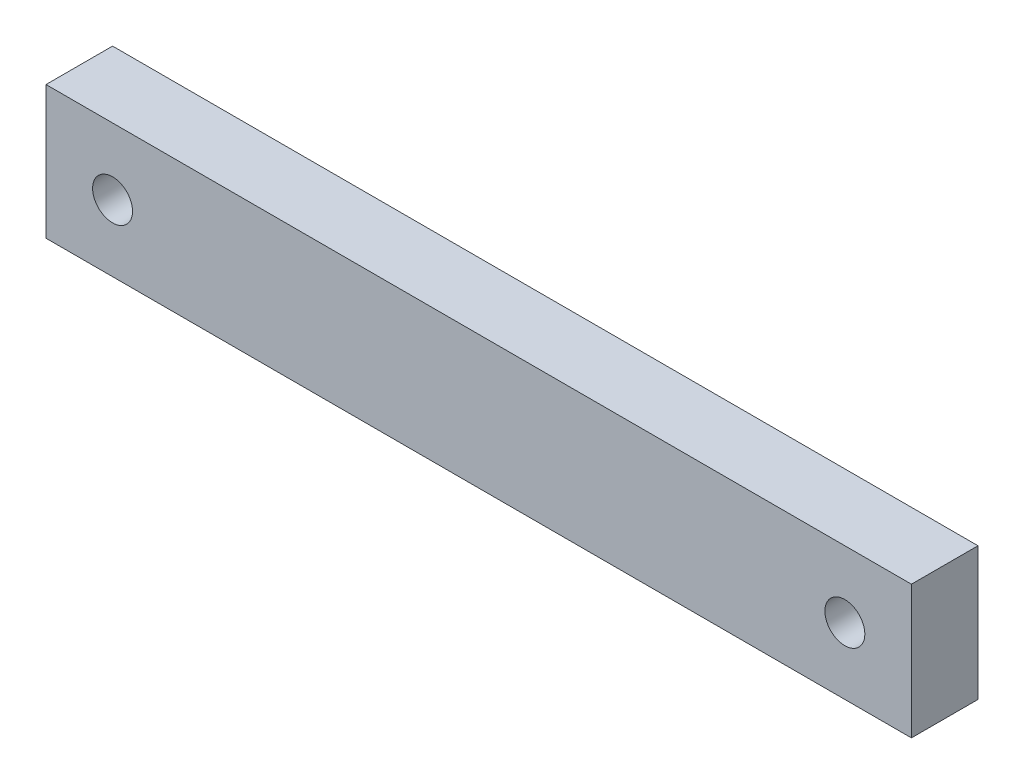
SolidWorks part; units mm, degrees
ref_plane "Front Plane" through (0, 0, 0) normal (0, 0, 1) x (1, 0, 0)
ref_plane "Top Plane" through (0, 0, 0) normal (0, 1, 0) x (1, 0, 0)
ref_plane "Right Plane" through (0, 0, 0) normal (1, 0, 0) x (0, 0, -1)
sketch "Sketch1" plane through (0, 0, 0) normal (0, 0, 1) x (1, 0, 0)
  line L0 (0, 0) -> (27.5, 0)
  line L1 (-32.5, 5) -> (32.5, 5)
  line L2 (-32.5, 5) -> (-32.5, -5)
  line L3 (-32.5, -5) -> (32.5, -5)
  line L4 (32.5, 5) -> (32.5, -5)
  line L5 (-32.5, 5) -> (32.5, -5) construction
  line L6 (-32.5, -5) -> (32.5, 5) construction
  line L7 (0, 0) -> (-27.5, 0)
  circle A0 centre (-27.5, 0) radius 1.5
  circle A1 centre (27.5, 0) radius 1.5
  point P0 (0, 0)
  dimension "D5" = 3
  dimension "D6" = 3
  dimension "D1" = 65
  dimension "D2" = 10
  dimension "D3" = 27.5
  dimension "D4" = 27.5
extrude "Boss-Extrude1" add sketch "Sketch1" along normal blind 5 contours L2 L1 L4 L3 | A0 | A1
